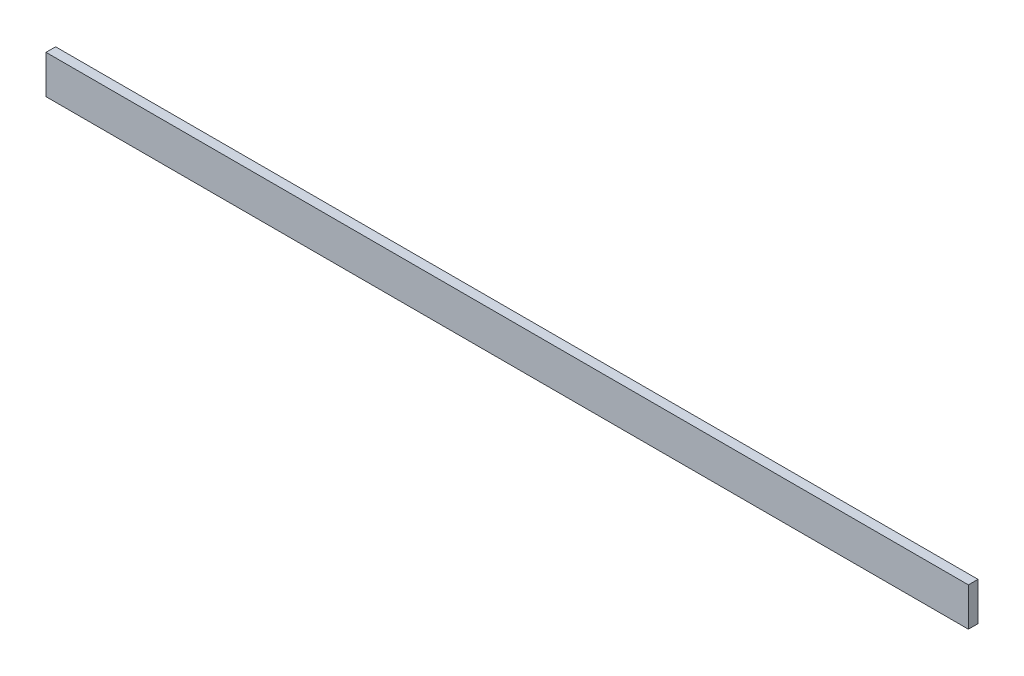
SolidWorks part; units mm, degrees
ref_plane "Front Plane" through (0, 0, 0) normal (0, 0, 1) x (1, 0, 0)
ref_plane "Top Plane" through (0, 0, 0) normal (0, 1, 0) x (1, 0, 0)
ref_plane "Right Plane" through (0, 0, 0) normal (1, 0, 0) x (0, 0, -1)
sketch "Sketch1" plane through (0, 0, 0) normal (0, 0, 1) x (1, 0, 0)
  line L2 (2226.2027, -7.4747) -> (-212.1973, -7.4747)
  line L3 (2226.2027, -7.4747) -> (2226.2027, 94.1253)
  line L4 (2226.2027, 94.1253) -> (-212.1973, 94.1253)
  line L5 (-212.1973, -7.4747) -> (-212.1973, 94.1253)
  dimension "D1" = 101.6
  dimension "D2" = 2438.4
extrude "Boss-Extrude1" add sketch "Sketch1" along normal blind 25.4
